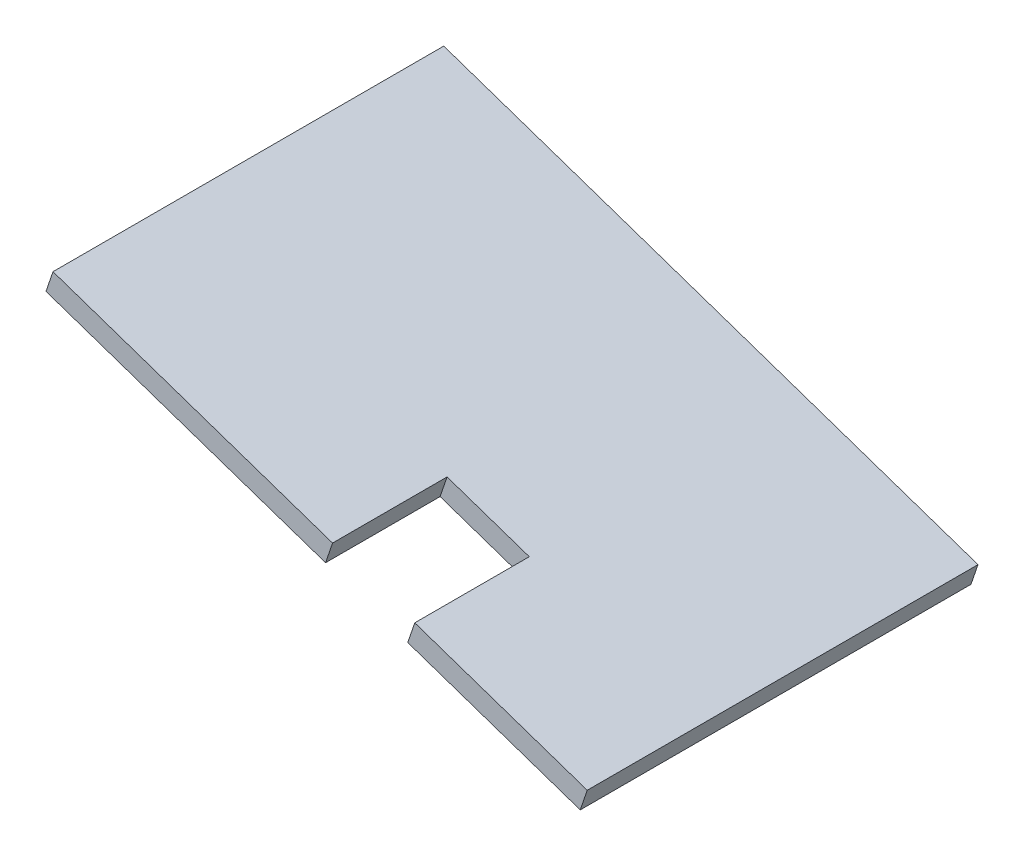
SolidWorks part; units mm, degrees
material "Plain Carbon Steel"
ref_plane "Front Plane" through (0, 0, 0) normal (0, 0, 1) x (1, 0, 0)
ref_plane "Top Plane" through (0, 0, 0) normal (0, 1, 0) x (1, 0, 0)
ref_plane "Right Plane" through (0, 0, 0) normal (1, 0, 0) x (0, 0, -1)
sketch "Sketch1" plane through (0, 0, 0) normal (0, 0, 1) x (1, 0, 0)
  line L4 (581.8088, 79.428) -> (425.5379, 132.6516)
  line L5 (581.8088, 79.428) -> (579.7615, 73.4171)
  line L6 (425.5379, 132.6516) -> (423.4906, 126.6407)
  line L7 (579.7615, 73.4171) -> (423.4906, 126.6407)
  dimension "D1" = 6.35
ref_plane "Plane1" through (0, 0, -21.8802) normal (0, 0, -1) x (-1, 0, 0)
extrude "Boss-Extrude2" add sketch "Sketch1" against normal blind 114.3
sketch "Sketch2" plane through (84.7143, 248.7313, 0) normal (0.3224, 0.9466, 0) x (0.9466, -0.3224, 0)
  line L6 (446.4372, 33.4985) -> (471.8372, 33.4985)
  line L7 (446.4372, 33.4985) -> (446.4372, -7.2984)
  line L8 (471.8372, 33.4985) -> (471.8372, -7.2984)
  line L9 (446.4372, -7.2984) -> (471.8372, -7.2984)
extrude "Cut-Extrude1" cut sketch "Sketch2" against normal up to next
